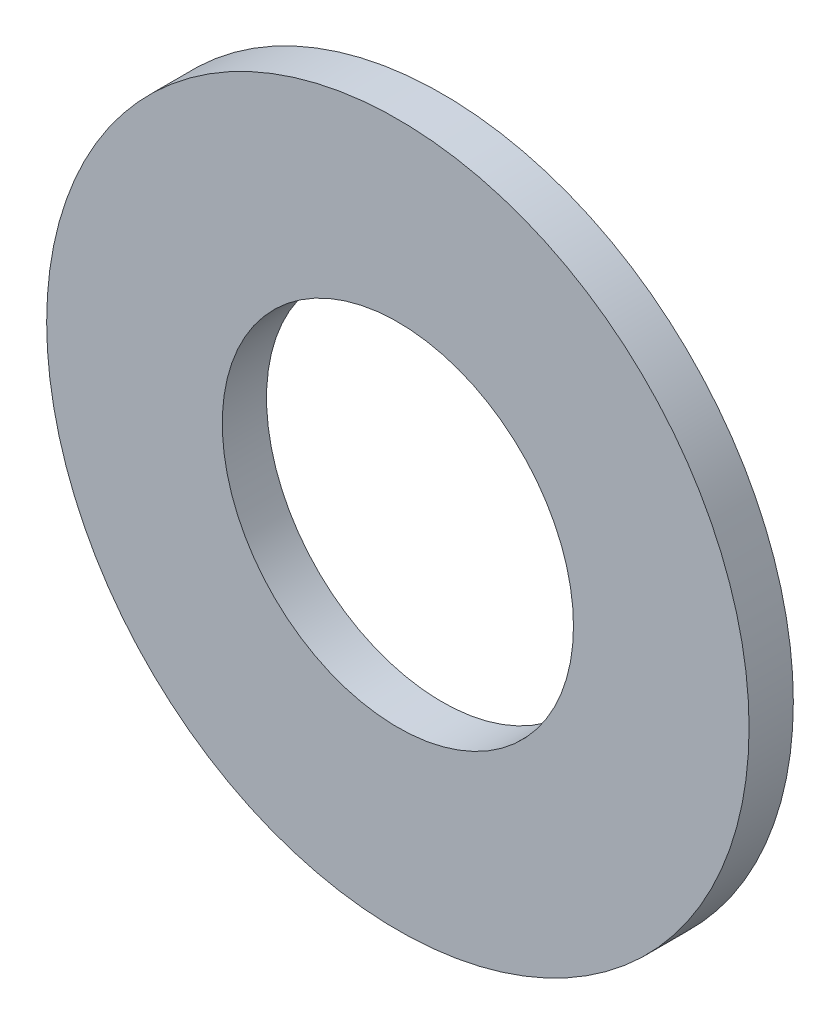
SolidWorks part; units mm, degrees
ref_plane "Front Plane" through (0, 0, 0) normal (0, 0, 1) x (1, 0, 0)
ref_plane "Top Plane" through (0, 0, 0) normal (0, 1, 0) x (1, 0, 0)
ref_plane "Right Plane" through (0, 0, 0) normal (1, 0, 0) x (0, 0, -1)
sketch "Sketch1" plane through (0, 0, 0) normal (0, 0, 1) x (1, 0, 0)
  circle A0 centre (0, 0) radius 12.7
  circle A1 centre (0, 0) radius 6.35
  dimension "D1" = 12.7
  dimension "D2" = 25.4
extrude "Boss-Extrude1" add sketch "Sketch1" along normal blind 1.6002
